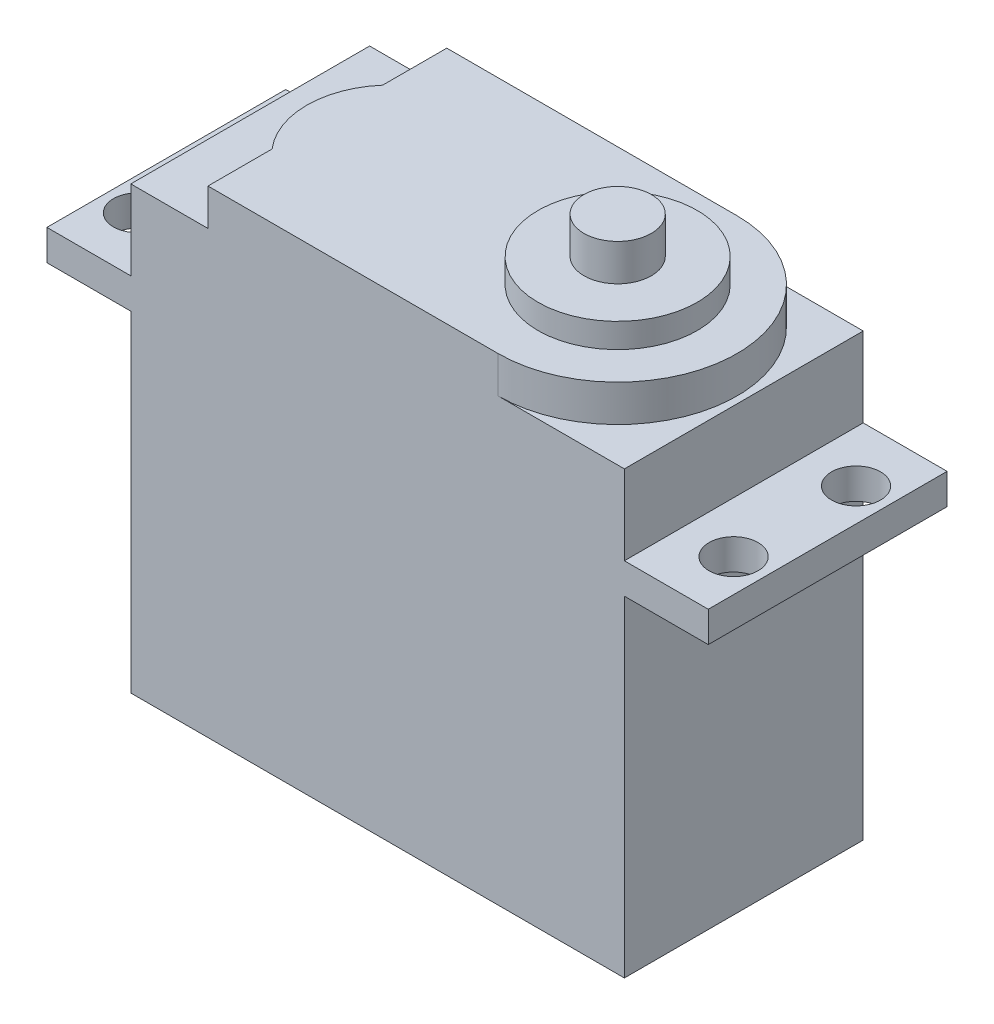
SolidWorks part; units mm, degrees
ref_plane "Front Plane" through (0, 0, 0) normal (0, 0, 1) x (1, 0, 0)
ref_plane "Top Plane" through (0, 0, 0) normal (0, 1, 0) x (1, 0, 0)
ref_plane "Right Plane" through (0, 0, 0) normal (1, 0, 0) x (0, 0, -1)
sketch "Sketch1" plane through (0, 0, 0) normal (0, 1, 0) x (1, 0, 0)
  line L1 (-20.15, 9.75) -> (20.15, 9.75)
  line L2 (-20.15, 9.75) -> (-20.15, -9.75)
  line L3 (-20.15, -9.75) -> (20.15, -9.75)
  line L4 (20.15, 9.75) -> (20.15, -9.75)
  line L5 (-20.15, 9.75) -> (20.15, -9.75) construction
  line L6 (-20.15, -9.75) -> (20.15, 9.75) construction
  point P0 (0, 0)
  dimension "D1" = 40.3
  dimension "D2" = 19.5
extrude "Boss-Extrude1" add sketch "Sketch1" along normal blind 27
sketch "Sketch2" plane through (0, 27, 0) normal (0, 1, 0) x (1, 0, 0)
  line L1 (-27, 9.75) -> (27, 9.75)
  line L2 (-27, 9.75) -> (-27, -9.75)
  line L3 (-27, -9.75) -> (27, -9.75)
  line L4 (27, 9.75) -> (27, -9.75)
  line L5 (-27, 9.75) -> (27, -9.75) construction
  line L6 (-27, -9.75) -> (27, 9.75) construction
  point P0 (0, 0)
  dimension "D1" = 19.5
  dimension "D2" = 54
extrude "Boss-Extrude2" add sketch "Sketch2" along normal blind 2.5
sketch "Sketch3" plane through (0, 29.5, 0) normal (0, 1, 0) x (1, 0, 0)
  line L1 (-20.15, 9.75) -> (20.15, 9.75)
  line L2 (-20.15, 9.75) -> (-20.15, -9.75)
  line L3 (-20.15, -9.75) -> (20.15, -9.75)
  line L4 (20.15, 9.75) -> (20.15, -9.75)
  line L5 (-20.15, 9.75) -> (20.15, -9.75) construction
  line L6 (-20.15, -9.75) -> (20.15, 9.75) construction
  point P0 (0, 0)
  dimension "D1" = 19.5
  dimension "D2" = 40.3
extrude "Boss-Extrude3" add sketch "Sketch3" along normal blind 6.5
sketch "Sketch4" plane through (0, 36, 0) normal (0, 1, 0) x (1, 0, 0)
  line L0 (-20.15, 0) -> (20.15, 0) construction
  line L1 (-20.15, 9.75) -> (-20.15, -9.75) construction
  line L2 (20.15, -9.75) -> (20.15, 9.75) construction
  line L3 (0, 9.75) -> (0, -9.75) construction
  line L4 (20.15, 9.75) -> (-20.15, 9.75) construction
  line L5 (-20.15, -9.75) -> (20.15, -9.75) construction
  circle A0 centre (9.85, 0) radius 2.75
  dimension "D2" = 5.5
  dimension "D1" = 9.85
extrude "Boss-Extrude4" add sketch "Sketch4" along normal blind 8
sketch "Sketch5" plane through (0, 29.5, 0) normal (0, 1, 0) x (1, 0, 0)
  line L0 (-27, 0) -> (27, 0) construction
  line L1 (-27, 9.75) -> (-27, -9.75) construction
  line L2 (27, -9.75) -> (27, 9.75) construction
  line L3 (0, 0) -> (0, 15.0528) construction
  line L4 (-24.315, 0) -> (-24.315, 14.5347) construction
  circle A0 centre (-24.315, 5) radius 2
  circle A1 centre (-24.315, -5) radius 2
  circle A2 centre (24.315, -5) radius 2
  circle A3 centre (24.315, 5) radius 2
  dimension "D2" = 4
  dimension "D1" = 24.315
  dimension "D3" = 5
extrude "Cut-Extrude1" cut sketch "Sketch5" against normal through all both and the other way through all
sketch "Sketch6" plane through (0, 36, 0) normal (0, 1, 0) x (1, 0, 0)
  line L0 (20.15, 9.75) -> (-20.15, 9.75) construction
  line L1 (9.85, -9.75) -> (-13.85, -9.75)
  line L2 (20.15, -9.75) -> (20.15, 9.75) construction
  line L3 (9.85, 9.75) -> (-13.85, 9.75)
  line L4 (-13.85, -9.75) -> (-13.85, 9.75)
  arc A0 (9.85, -9.75) -> (9.85, 9.75) centre (9.85, 0) ccw
  dimension "D1" = 34
  dimension "D2" = 19.5
extrude "Boss-Extrude5" add sketch "Sketch6" along normal blind 3
sketch "Sketch7" plane through (0, 39, 0) normal (0, 1, 0) x (1, 0, 0)
  circle A0 centre (9.85, 0) radius 6.5
  dimension "D1" = 13
extrude "Boss-Extrude6" add sketch "Sketch7" along normal blind 2
sketch "Sketch8" plane through (0, 36, 0) normal (0, 1, 0) x (1, 0, 0)
  line L0 (-13.85, 0) -> (-20.15, 0) construction
  line L1 (-13.85, 9.75) -> (-13.85, -9.75) construction
  line L2 (-20.15, 9.75) -> (-20.15, -9.75) construction
  line L3 (-13.85, 4.5109) -> (-13.85, -4.5109)
  arc A0 (-13.85, -4.5109) -> (-13.85, 4.5109) centre (-8.6351, 0) cw
extrude "Boss-Extrude7" add sketch "Sketch8" along normal blind 3
